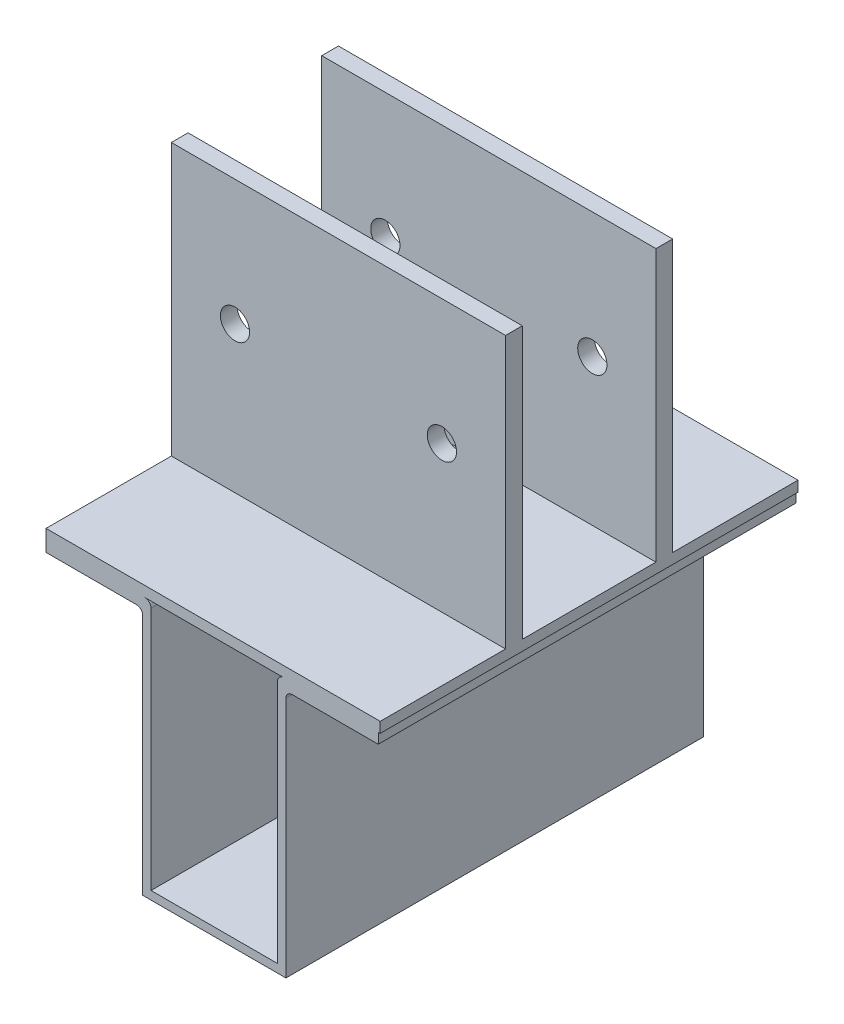
SolidWorks part; units mm, degrees
ref_plane "Alzado" through (0, 0, 0) normal (0, 0, 1) x (1, 0, 0)
ref_plane "Planta" through (0, 0, 0) normal (0, 1, 0) x (1, 0, 0)
ref_plane "Vista lateral" through (0, 0, 0) normal (1, 0, 0) x (0, 0, -1)
sketch "Croquis1" plane through (0, 0, 0) normal (0, 1, 0) x (1, 0, 0)
  line L1 (40, -100) -> (-40, -100)
  line L2 (40, -100) -> (40, 100)
  line L3 (40, 100) -> (-40, 100)
  line L4 (-40, -100) -> (-40, 100)
  line L5 (40, -100) -> (-40, 100) construction
  line L6 (40, 100) -> (-40, -100) construction
  point P0 (0, 0)
  dimension "D1" = 200
  dimension "D2" = 80
extrude "Saliente-Extruir1" add sketch "Croquis1" along normal blind 5
sketch "Croquis2" plane through (0, 5, 0) normal (0, 1, 0) x (1, 0, 0)
  line L1 (40, -32) -> (-40, -32) construction
  line L2 (40, -32) -> (40, 32) construction
  line L3 (40, 32) -> (-40, 32) construction
  line L4 (-40, -32) -> (-40, 32) construction
  line L5 (40, -32) -> (-40, 32) construction
  line L6 (40, 32) -> (-40, -32) construction
  line L7 (-40, 100) -> (-40, -100) construction
  line L9 (-40, -32) -> (40, -32)
  line L10 (-40, -32) -> (-40, -40)
  line L11 (-40, -40) -> (40, -40)
  line L12 (40, -32) -> (40, -40)
  line L13 (40, -100) -> (40, 100) construction
  line L15 (40, 32) -> (-40, 32)
  line L16 (40, 32) -> (40, 40)
  line L17 (40, 40) -> (-40, 40)
  line L18 (-40, 32) -> (-40, 40)
  point P0 (0, 0)
  dimension "D1" = 64
  dimension "D2" = 80
  dimension "D3" = 8
  dimension "D4" = 80
  dimension "D5" = 8
  dimension "D6" = 80
extrude "Saliente-Extruir2" add sketch "Croquis2" along normal blind 130
sketch "Croquis3" plane through (0, 0, 40) normal (0, 0, 1) x (1, 0, 0)
  line L0 (-40, 135) -> (40, 135) construction
  circle A0 centre (-9.5392, 75) radius 7
  dimension "D1" = 60
extrude "Cortar-Extruir1" cut sketch "Croquis3" against normal through all
mirror "Simetría1" about plane through (40, 5, 100) normal (-1, 0, 0) of "Cortar-Extruir1", "Saliente-Extruir1", "Saliente-Extruir2"
sketch "Croquis4" plane through (0, 0, -100) normal (0, 0, -1) x (-1, 0, 0)
  line L1 (-6.2712, -7.9778) -> (-6.2712, -124)
  line L2 (-10.2712, -3) -> (-10.2712, -120)
  line L3 (-10.2712, -120) -> (-70.8451, -120)
  line L4 (-70.8451, -3) -> (-70.8451, -120)
  line L5 (-6.2712, -124) -> (-74.8451, -124)
  line L6 (-73.8451, 0) -> (-119.057, 0)
  line L7 (-70.8451, -3) -> (-70.8451, -4.9778)
  line L8 (-77.8451, -4.9778) -> (-119.057, -4.9778)
  line L9 (-119.057, 0) -> (-119.057, -4.9778)
  line L10 (-7.2712, 0) -> (40.001, 0)
  line L11 (-10.2712, -3) -> (-10.2712, -4.9778)
  line L12 (-3.2712, -4.9778) -> (40.001, -4.9778)
  line L13 (40.001, 0) -> (40.001, -4.9778)
  line L14 (-74.8451, -7.9778) -> (-74.8451, -124)
  line L15 (-70.8451, 0) -> (-70.8451, -120) construction
  line L16 (-6.2712, 0) -> (-6.2712, -124) construction
  line L17 (-74.8451, 0) -> (-74.8451, -124) construction
  line L18 (-10.2712, 0) -> (-10.2712, -120) construction
  arc A0 (-74.8451, -7.9778) -> (-77.8451, -4.9778) centre (-77.8451, -7.9778) ccw
  arc A1 (-73.8451, 0) -> (-70.8451, -3) centre (-73.8451, -3) cw
  arc A2 (-7.2712, 0) -> (-10.2712, -3) centre (-7.2712, -3) ccw
  arc A3 (-6.2712, -7.9778) -> (-3.2712, -4.9778) centre (-3.2712, -7.9778) cw
  line M2 (-120, 0) -> (40, 0)
  dimension "D8" = 3
  dimension "D7" = 4
extrude "Saliente-Extruir3" add sketch "Croquis4" against normal blind 200 contours L1 A3 L12 L13 L10 A2 L2 L3 L4 A1 L9 L8 A0 L14 L5 M2
